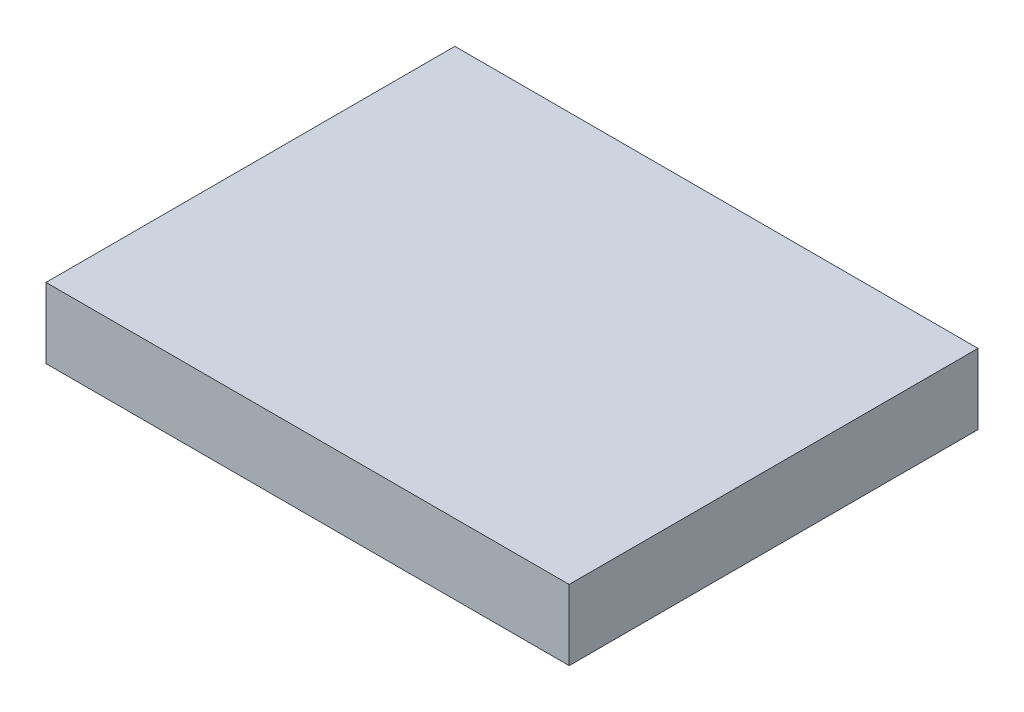
SolidWorks part; units mm, degrees
ref_plane "Front Plane" through (0, 0, 0) normal (0, 0, 1) x (1, 0, 0)
ref_plane "Top Plane" through (0, 0, 0) normal (0, 1, 0) x (1, 0, 0)
ref_plane "Right Plane" through (0, 0, 0) normal (1, 0, 0) x (0, 0, -1)
sketch "Sketch1" plane through (0, 0, 0) normal (0, 1, 0) x (1, 0, 0)
  line L1 (59.5, 46.5) -> (-59.5, 46.5)
  line L2 (59.5, 46.5) -> (59.5, -46.5)
  line L3 (59.5, -46.5) -> (-59.5, -46.5)
  line L4 (-59.5, 46.5) -> (-59.5, -46.5)
  line L5 (0, -46.5) -> (0, 46.5) construction
  line L6 (59.5, 0) -> (-59.5, 0) construction
  point P0 (0, 0)
  dimension "D1" = 119
  dimension "D2" = 93
extrude "Boss-Extrude1" add sketch "Sketch1" along normal blind 16
